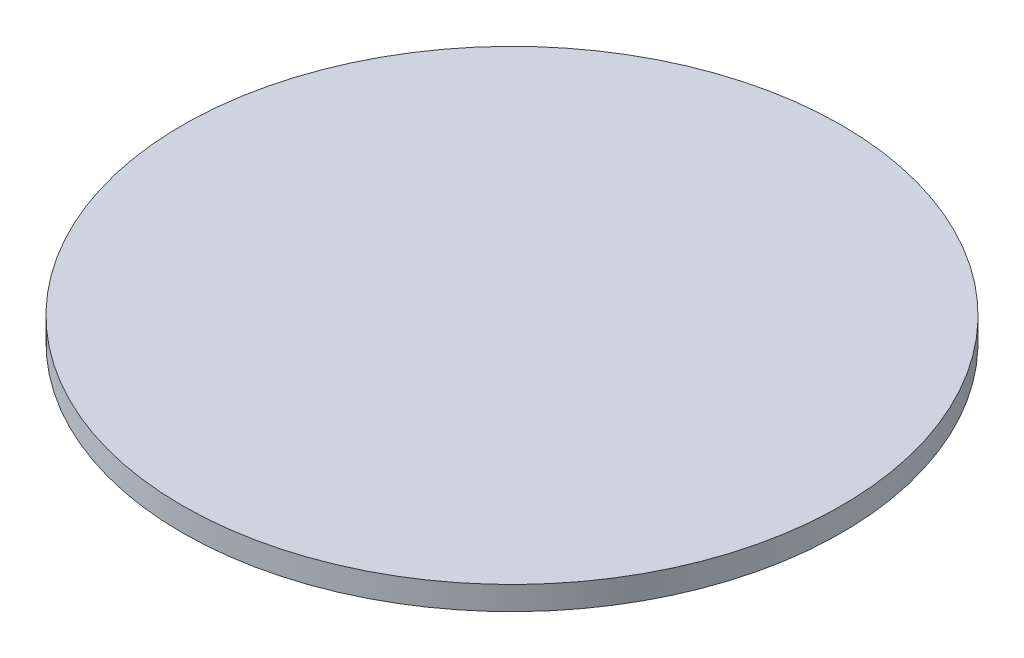
SolidWorks part; units mm, degrees
ref_plane "Front Plane" through (0, 0, 0) normal (0, 0, 1) x (1, 0, 0)
ref_plane "Top Plane" through (0, 0, 0) normal (0, 1, 0) x (1, 0, 0)
ref_plane "Right Plane" through (0, 0, 0) normal (1, 0, 0) x (0, 0, -1)
sketch "Sketch1" plane through (0, 0, 0) normal (0, 1, 0) x (1, 0, 0)
  circle A0 centre (0, 0) radius 88.9
  dimension "D1" = 177.8
extrude "Boss-Extrude1" add sketch "Sketch1" along normal blind 6.35
